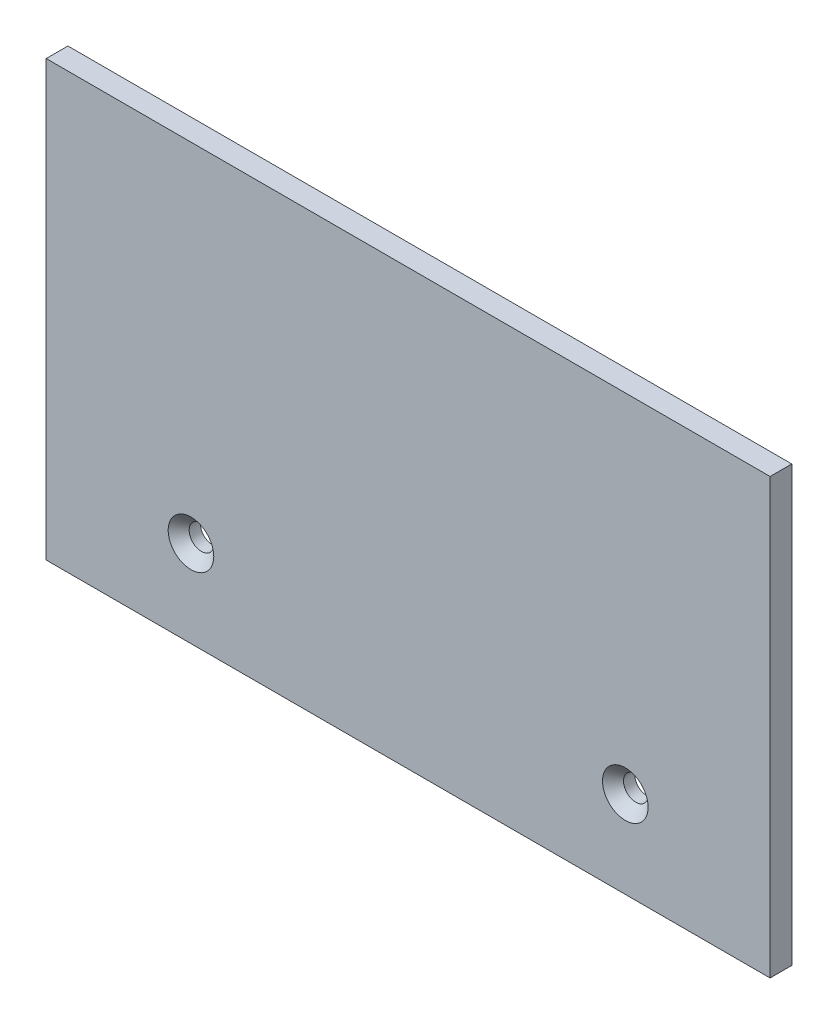
SolidWorks part; units mm, degrees
ref_plane "Front Plane" through (0, 0, 0) normal (0, 0, 1) x (1, 0, 0)
ref_plane "Top Plane" through (0, 0, 0) normal (0, 1, 0) x (1, 0, 0)
ref_plane "Right Plane" through (0, 0, 0) normal (1, 0, 0) x (0, 0, -1)
sketch "Sketch1" plane through (0, 0, 0) normal (0, 0, 1) x (1, 0, 0)
  line L1 (50, 30) -> (-50, 30)
  line L2 (50, 30) -> (50, -30)
  line L3 (50, -30) -> (-50, -30)
  line L4 (-50, 30) -> (-50, -30)
  line L5 (50, 30) -> (-50, -30) construction
  line L6 (50, -30) -> (-50, 30) construction
  point P0 (0, 0)
  dimension "D1" = 60
  dimension "D2" = 100
extrude "Boss-Extrude1" add sketch "Sketch1" along normal mid plane 3
sketch "Sketch2" plane through (0, 0, 1.5) normal (0, 0, 1) x (1, 0, 0)
  line L0 (-30, -18) -> (30, -18) construction
  line L1 (-50, 30) -> (-50, -30) construction
  line L2 (50, -30) -> (50, 30) construction
  line L3 (-50, -30) -> (50, -30) construction
  point P0 (-30, -18)
  point P1 (30, -18)
  dimension "D1" = 20
  dimension "D2" = 20
  dimension "D3" = 12
hole_wizard "CSK for M3 Countersunk Flat Head Screw1" positions "Sketch2" profile "Sketch3" countersink size "M3" standard "ISO" end condition through all
sketch "Sketch3" plane through (-30, -18, 1.5) normal (1, 0, 0) x (0, -1, 0)
  line L0 (0, 0) -> (0, 3)
  line L1 (0, 3) -> (1.7, 3)
  line L2 (1.7, 3) -> (1.7, 1.45)
  line L3 (1.7, 1.45) -> (3.15, 0)
  line L5 (3.15, 0) -> (0, 0)
  line L6 (-1.7, 1.45) -> (-3.15, 0) construction
  line L11 (0, -6.35) -> (0, 107.95) construction
  dimension "Thru Hole Dia." = 3.4
  dimension "Thru Hole Depth" = 3
  dimension "Near C'Sink Dia." = 6.3
  dimension "Near C'Sink Angle" = 90
sketch "Sketch4" plane through (0, 0, 0) normal (0, 0, 1) x (1, 0, 0)
  line L1 (50, -30) -> (65, -30)
  line L2 (50, -30) -> (50, 30)
  line L3 (50, 30) -> (65, 30)
  line L4 (65, -30) -> (65, 30)
  dimension "D1" = 15
extrude "Boss-Extrude2" [suppressed] add sketch "Sketch4" along normal mid plane 3
